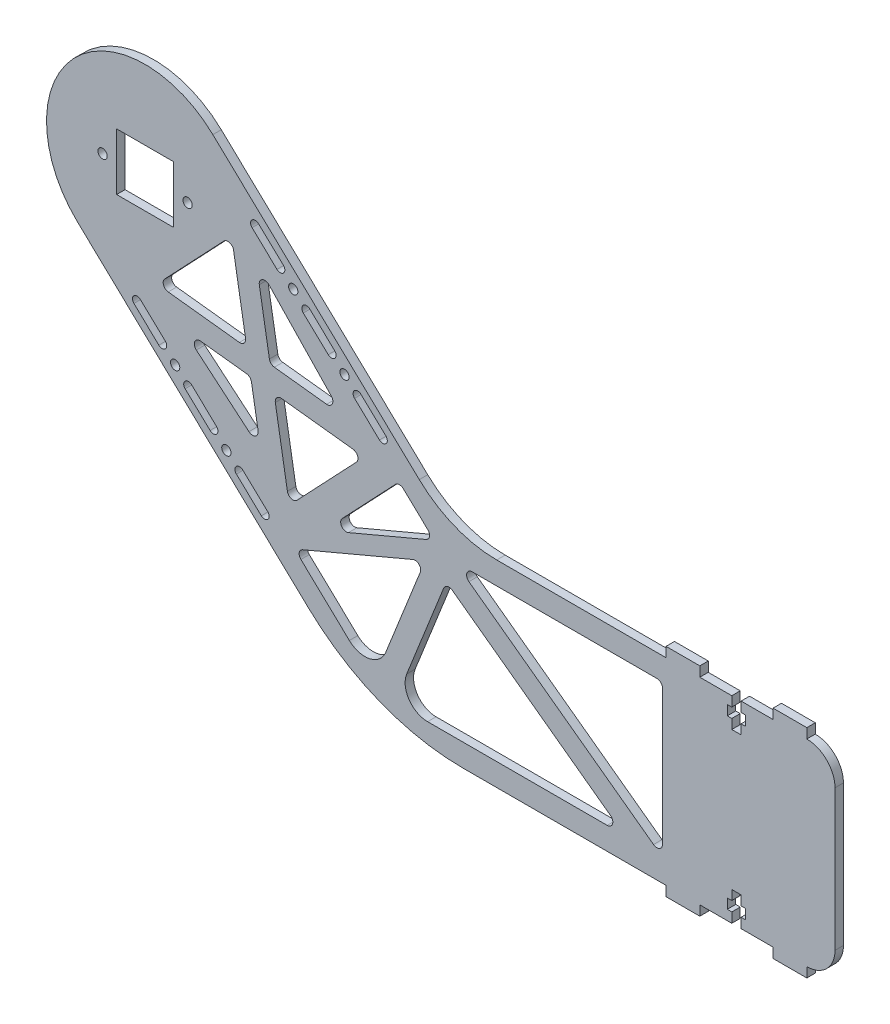
SolidWorks part; units mm, degrees
material "Thornel Mat VMA"
ref_plane "前视基准面" through (0, 0, 0) normal (0, 0, 1) x (1, 0, 0)
ref_plane "上视基准面" through (0, 0, 0) normal (0, 1, 0) x (1, 0, 0)
ref_plane "右视基准面" through (0, 0, 0) normal (1, 0, 0) x (0, 0, -1)
sketch "草图1" plane through (0, 0, 0) normal (0, 0, 1) x (1, 0, 0)
  line L0 (0, 0) -> (95, -90) construction
  line L1 (95, -90) -> (245, -90) construction
  line L2 (-24.0711, -25.4083) -> (81.0535, -125)
  line L3 (81.0535, -125) -> (245, -125)
  line L4 (24.0711, 25.4083) -> (108.9465, -55)
  line L5 (108.9465, -55) -> (245, -55)
  line L6 (245, -55) -> (245, -125)
  circle A1 centre (0, 0) radius 7.65
  circle A2 centre (0, 0) radius 35
  dimension "D6" = 15.3
  dimension "D1" = 150
  dimension "D2" = 245
  dimension "D3" = 90
  dimension "D4" = 35
  dimension "D5" = 35
extrude "凸台-拉伸1" add sketch "草图1" along normal blind 3
sketch "草图3" plane through (0, 0, 3) normal (0, 0, 1) x (1, 0, 0)
  line L0 (210, -55) -> (210, -125) construction
  line L2 (108.9465, -55) -> (245, -55) construction
  line L5 (81.0535, -125) -> (245, -125) construction
  line L8 (245, -90) -> (97.2271, -90) construction
  line L9 (245, -55) -> (245, -125) construction
  line L12 (39.125, 4.9479) -> (47.9817, -3.4425) construction
  line L13 (40.2598, 6.1458) -> (49.1164, -2.2447)
  line L14 (37.9903, 3.7501) -> (46.8469, -4.6404)
  line L15 (-2.7794, -39.2843) -> (102.3452, -138.876) construction
  line L16 (15.3695, -56.4779) -> (24.2261, -64.8684) construction
  line L17 (16.5042, -55.2801) -> (25.3609, -63.6706)
  line L18 (-20.9762, -22.1416) -> (84.1483, -121.7332)
  line L19 (-20.9762, -22.1416) -> (84.1483, -121.7332) construction
  line L20 (208.35, -55) -> (208.35, -58.5)
  line L21 (20.9762, 22.1416) -> (105.8517, -58.2668)
  line L22 (20.9762, 22.1416) -> (105.8517, -58.2668) construction
  line L25 (208.35, -58.5) -> (206.75, -58.5)
  line L28 (206.75, -58.5) -> (206.75, -62)
  line L31 (206.75, -62) -> (208.35, -62)
  line L34 (14.2347, -57.6758) -> (23.0913, -66.0662)
  line L37 (-2.8274, -39.3352) -> (6.0292, -47.7257) construction
  line L38 (-1.6926, -38.1374) -> (7.164, -46.5278)
  line L39 (-3.9622, -40.533) -> (4.8944, -48.9235)
  line L40 (57.3219, -12.1948) -> (66.1785, -20.5853) construction
  line L41 (58.4567, -10.997) -> (67.3133, -19.3875)
  line L42 (56.1871, -13.3926) -> (65.0437, -21.7831)
  line L43 (15.4175, -56.4271) -> (120.542, -156.0187) construction
  line L44 (33.5663, -73.6207) -> (42.4229, -82.0112) construction
  line L45 (34.7011, -72.4229) -> (43.5577, -80.8134)
  line L46 (32.4315, -74.8185) -> (41.2882, -83.209)
  line L47 (75.5187, -29.3376) -> (84.3754, -37.7281) construction
  line L48 (76.6535, -28.1398) -> (85.5101, -36.5303)
  line L49 (74.384, -30.5354) -> (83.2406, -38.9259)
  line L50 (208.35, -62) -> (208.35, -65.4)
  line L51 (208.35, -65.4) -> (211.65, -65.4)
  line L52 (211.65, -65.4) -> (211.65, -62)
  line L53 (211.65, -62) -> (213.25, -62)
  line L54 (213.25, -62) -> (213.25, -58.5)
  line L55 (213.25, -58.5) -> (211.65, -58.5)
  line L56 (211.65, -58.5) -> (211.65, -55)
  line L57 (208.35, -55) -> (211.65, -55)
  line L58 (208.35, -125) -> (211.65, -125)
  line L59 (211.65, -121.5) -> (211.65, -125)
  line L60 (213.25, -121.5) -> (211.65, -121.5)
  line L61 (213.25, -118) -> (213.25, -121.5)
  line L62 (211.65, -118) -> (213.25, -118)
  line L63 (211.65, -114.6) -> (211.65, -118)
  line L64 (208.35, -114.6) -> (211.65, -114.6)
  line L65 (208.35, -118) -> (208.35, -114.6)
  line L66 (206.75, -118) -> (208.35, -118)
  line L67 (206.75, -121.5) -> (206.75, -118)
  line L68 (208.35, -121.5) -> (206.75, -121.5)
  line L69 (208.35, -125) -> (208.35, -121.5)
  arc A23 (-1.6926, -38.1374) -> (-3.9622, -40.533) centre (-2.8274, -39.3352) ccw
  arc A24 (4.8944, -48.9235) -> (7.164, -46.5278) centre (6.0292, -47.7257) ccw
  circle A25 centre (10.6753, -52.1272) radius 1.65
  arc A26 (40.2598, 6.1458) -> (37.9903, 3.7501) centre (39.125, 4.9479) ccw
  arc A27 (46.8469, -4.6404) -> (49.1164, -2.2447) centre (47.9817, -3.4425) ccw
  circle A28 centre (52.6277, -7.8441) radius 1.65
  circle A29 centre (70.8246, -24.9869) radius 1.65
  circle A30 centre (28.8722, -69.27) radius 1.65
  arc A31 (16.5042, -55.2801) -> (14.2347, -57.6758) centre (15.3695, -56.4779) ccw
  arc A32 (23.0913, -66.0662) -> (25.3609, -63.6706) centre (24.2261, -64.8684) ccw
  arc A33 (58.4567, -10.997) -> (56.1871, -13.3926) centre (57.3219, -12.1948) ccw
  arc A34 (65.0437, -21.7831) -> (67.3133, -19.3875) centre (66.1785, -20.5853) ccw
  arc A37 (34.7011, -72.4229) -> (32.4315, -74.8185) centre (33.5663, -73.6207) ccw
  arc A38 (41.2882, -83.209) -> (43.5577, -80.8134) centre (42.4229, -82.0112) ccw
  arc A39 (76.6535, -28.1398) -> (74.384, -30.5354) centre (75.5187, -29.3376) ccw
  arc A40 (83.2406, -38.9259) -> (85.5101, -36.5303) centre (84.3754, -37.7281) ccw
  circle A41 centre (89.0215, -42.1296) radius 1.65 [skipped]
  circle A42 centre (47.069, -86.4128) radius 1.65 [skipped]
  point P21 (213.9, -120.5)
  point P38 (188.9, -120.5)
  point P68 (43.5533, 0.7527)
  point P81 (1.6009, -43.5304)
  point P93 (61.7502, -16.3901)
  point P102 (19.7978, -60.6732)
  point P113 (79.9471, -33.5328)
  point P122 (37.9946, -77.8159)
  dimension "D8" = 3.5
  dimension "D9" = 3.4
  dimension "D10" = 35
  dimension "D14" = 3.3
  dimension "D16" = 3.3
  dimension "D18" = 6.4
  dimension "D22" = 3.3
  dimension "D23" = 6.4
  dimension "D3" = 3.3
  dimension "D4" = 6.5
  dimension "D5" = 3.5
  dimension "D15" = 12.2
  dimension "D17" = 25
  dimension "D19" = 25
  dimension "D20" = 12.2
  dimension "D21" = 3.3
  dimension "D25" = 12.8001
  dimension "D6" = 4.5
  dimension "D7" = 4.5
  dimension "D24" = 3
fillet "圆角1" radius 10 2 edges at (245, -125, 1.5) (245, -55, 1.5)
extrude "切除-拉伸2" cut sketch "草图3" against normal through all
fillet "圆角2" radius 40 1 edges at (108.9465, -55, 1.5)
fillet "圆角3" radius 80 1 edges at (81.0535, -125, 1.5)
sketch "草图4" plane through (0, 0, 3) normal (0, 0, 1) x (1, 0, 0)
  line L0 (211.65, -55) -> (235, -55) construction
  line L1 (223, -55) -> (235, -55)
  line L2 (223, -55) -> (223, -51.5)
  line L3 (223, -51.5) -> (235, -51.5)
  line L4 (235, -55) -> (235, -51.5)
  line L5 (124.8854, -55) -> (208.35, -55) construction
  line L6 (197, -55) -> (185, -55)
  line L7 (197, -55) -> (197, -51.5)
  line L8 (197, -51.5) -> (185, -51.5)
  line L9 (185, -55) -> (185, -51.5)
  line L10 (210, -114.6) -> (210, -65.4) construction
  line L11 (211.65, -114.6) -> (208.35, -114.6) construction
  line L12 (208.35, -65.4) -> (211.65, -65.4) construction
  line L13 (245, -90) -> (145.9271, -90) construction
  line L14 (245, -65) -> (245, -115) construction
  line L15 (185, -125) -> (185, -128.5)
  line L16 (197, -128.5) -> (185, -128.5)
  line L17 (197, -125) -> (197, -128.5)
  line L18 (197, -125) -> (185, -125)
  line L19 (235, -125) -> (235, -128.5)
  line L20 (223, -128.5) -> (235, -128.5)
  line L21 (223, -125) -> (223, -128.5)
  line L22 (223, -125) -> (235, -125)
  dimension "D1" = 12
  dimension "D2" = 3.5
  dimension "D3" = 12
  dimension "D4" = 3.5
  dimension "D5" = 50
extrude "凸台-拉伸2" add sketch "草图4" against normal blind 3
sketch "草图5" plane through (0, 0, 3) normal (0, 0, 1) x (1, 0, 0)
  line L0 (206.75, -58.5) -> (206.75, -62) construction
  line L1 (112.9313, -125) -> (185, -125) construction
  line L2 (124.8854, -55) -> (185, -55) construction
  line L3 (43.5577, -80.8134) -> (34.7011, -72.4229) construction
  line L5 (74.384, -30.5354) -> (83.2406, -38.9259) construction
  line L6 (-24.0711, -25.4083) -> (57.9117, -103.0762) construction
  line L7 (110.0646, -63) -> (183.75, -63)
  line L8 (183.75, -63) -> (183.75, -117)
  line L20 (30.3625, 5.8657) -> (-10.9022, -37.6914) construction
  line L21 (37.9102, 3.826) -> (32.9141, 8.5591) construction
  line L22 (183.75, -117) -> (110.0646, -63)
  line L23 (107.0057, -70.6766) -> (170.2161, -117)
  line L24 (170.2161, -117) -> (88.5471, -117)
  line L25 (88.5471, -117) -> (107.0057, -70.6766)
  line L26 (81.1154, -114.0387) -> (99.5099, -67.876)
  line L27 (99.5099, -67.876) -> (53.1169, -87.5138)
  line L28 (53.1169, -87.5138) -> (81.1154, -114.0387)
  line L29 (63.4218, -76.6364) -> (90.2551, -48.3123)
  line L30 (90.2551, -48.3123) -> (102.6329, -60.0387)
  line L31 (102.6329, -60.0387) -> (63.4218, -76.6364)
  line L32 (124.8854, -15) -> (83.3179, -119.3172) construction
  line L33 (92.8533, -39.7537) -> (51.5886, -83.3109) construction
  line L34 (82.2938, -38.0289) -> (88.7199, -44.1168) construction
  line L35 (39.4821, -76.9522) -> (49.037, -86.0043) construction
  line L36 (-0.6119, -38.9684) -> (-6.6725, -33.2268) construction
  line L37 (-6.6725, -33.2268) -> (88.7199, -44.1168) construction
  line L38 (88.7199, -44.1168) -> (32.9141, 8.5591) construction
  line L39 (32.9141, 8.5591) -> (49.037, -86.0043) construction
  line L40 (4.2277, -30.4452) -> (36.1275, -34.0869)
  line L41 (36.1275, -34.0869) -> (30.7359, -2.4644)
  line L42 (30.7359, -2.4644) -> (4.2277, -30.4452)
  line L43 (13.1295, -39.5134) -> (37.5275, -42.2987)
  line L44 (37.5275, -42.2987) -> (41.0634, -63.0369)
  line L45 (41.0634, -63.0369) -> (13.1295, -39.5134)
  line L46 (39.4655, -6.0664) -> (44.404, -35.0317)
  line L47 (44.404, -35.0317) -> (69.9504, -37.9481)
  line L48 (69.9504, -37.9481) -> (39.4655, -6.0664)
  line L49 (45.8041, -43.2435) -> (77.8196, -46.8984)
  line L50 (77.8196, -46.8984) -> (51.2152, -74.9808)
  line L51 (51.2152, -74.9808) -> (45.8041, -43.2435)
  line L52 (37.9903, 3.7501) -> (46.8469, -4.6404) construction
  line L53 (24.0711, 25.4083) -> (97.3757, -44.0381) construction
  arc A0 (103.9086, -45.8248) -> (118.9141, -51.804) centre (124.8854, -15) ccw construction
  arc A1 (97.3757, -44.0381) -> (124.8854, -55) centre (124.8854, -15) ccw construction
  arc A2 (97.3757, -44.0381) -> (124.8854, -55) centre (124.8854, -15) ccw
  arc A3 (57.9117, -103.0762) -> (112.9313, -125) centre (112.9313, -45) ccw construction
  dimension "D2" = 23
  dimension "D3" = 8
  dimension "D4" = 8
  dimension "D5" = 4
  dimension "D6" = 8
  dimension "D7" = 6
  dimension "D8" = 8
  dimension "D9" = 8
  dimension "D10" = 8
  dimension "D11" = 6
  dimension "D12" = 6
  dimension "D13" = 8
  dimension "D14" = 8
extrude "切除-拉伸3" cut sketch "草图5" against normal blind 10 contours L41 L42 L40 | L45 L44 L43 | L47 L48 L46 | L51 L50 L49 | L31 L30 L29 | L27 L28 L26 | L25 L24 L23 | L22 L8 L7
fillet "圆角4" radius 2 22 edges at (69.9504, -37.9481, 1.5) (44.404, -35.0317, 1.5) (39.4655, -6.0664, 1.5) (30.7359, -2.4644, 1.5) (36.1275, -34.0869, 1.5) (4.2277, -30.4452, 1.5) (13.1295, -39.5134, 1.5) (41.0634, -63.0369, 1.5) (37.5275, -42.2987, 1.5) (45.8041, -43.2435, 1.5) (51.2152, -74.9808, 1.5) (77.8196, -46.8984, 1.5) (90.2551, -48.3123, 1.5) (63.4218, -76.6364, 1.5) (53.1169, -87.5138, 1.5) (102.6329, -60.0387, 1.5) (99.5099, -67.876, 1.5) (107.0057, -70.6766, 1.5) (183.75, -63, 1.5) (110.0646, -63, 1.5) (183.75, -117, 1.5) (170.2161, -117, 1.5)
fillet "圆角5" radius 8 2 edges at (81.1154, -114.0387, 1.5) (88.5471, -117, 1.5)
sketch "草图6" plane through (0, 0, 3) normal (0, 0, 1) x (1, 0, 0)
  line L1 (10.1, -10.1) -> (-10.1, -10.1)
  line L2 (10.1, -10.1) -> (10.1, 10.1)
  line L3 (10.1, 10.1) -> (-10.1, 10.1)
  line L4 (-10.1, -10.1) -> (-10.1, 10.1)
  line L5 (10.1, -10.1) -> (-10.1, 10.1) construction
  line L6 (10.1, 10.1) -> (-10.1, -10.1) construction
  circle A0 centre (-15.1, 0) radius 1.65
  circle A1 centre (15.1, 0) radius 1.65
  point P0 (0, 0)
  point P10 (0, 0)
  point P11 (0, 0)
  point P12 (0, 0)
  dimension "D2" = 5
  dimension "D3" = 5
  dimension "D4" = 3.3
  dimension "D1" = 20.2
extrude "切除-拉伸4" cut sketch "草图6" against normal through all
